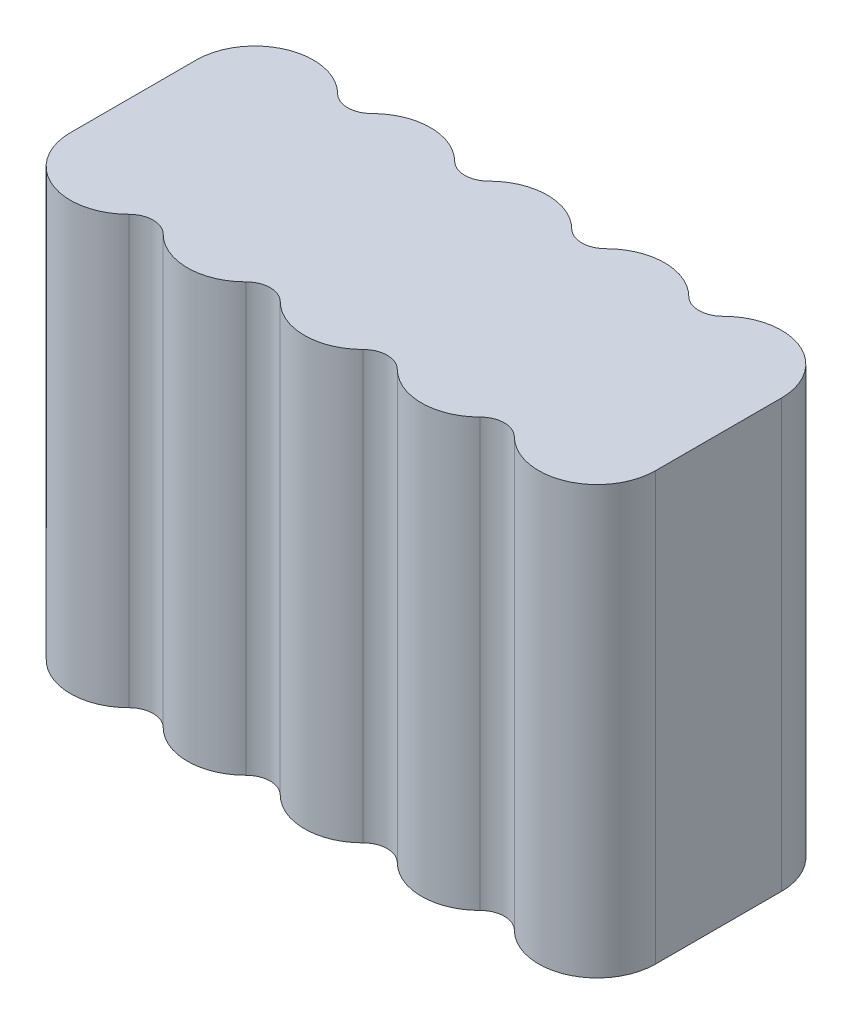
SolidWorks part; units mm, degrees
ref_plane "Front Plane" through (0, 0, 0) normal (0, 0, 1) x (1, 0, 0)
ref_plane "Top Plane" through (0, 0, 0) normal (0, 1, 0) x (1, 0, 0)
ref_plane "Right Plane" through (0, 0, 0) normal (1, 0, 0) x (0, 0, -1)
sketch "Sketch1" plane through (0, 0, 0) normal (0, 1, 0) x (1, 0, 0)
  line L0 (0, 23.139) -> (0, 7.341)
  line L1 (0, 0) -> (73.406, 0) construction
  line L2 (0, 0) -> (0, 30.48) construction
  line L3 (0, 30.48) -> (73.406, 30.48) construction
  line L4 (73.406, 0) -> (73.406, 30.48) construction
  line L5 (73.406, 23.139) -> (73.406, 7.341)
  arc A0 (14.6815, 23.0533) -> (14.6815, 23.2247) centre (7.341, 23.139) ccw
  arc A1 (0, 7.341) -> (12.5317, 2.15) centre (7.341, 7.341) ccw
  arc A2 (29.3625, 23.0533) -> (29.3625, 23.2247) centre (22.022, 23.139) ccw
  arc A3 (14.6815, 7.4267) -> (14.6815, 7.2553) centre (22.022, 7.341) ccw
  arc A4 (44.0435, 23.0533) -> (44.0435, 23.2247) centre (36.703, 23.139) ccw
  arc A5 (29.3625, 7.4267) -> (29.3625, 7.2553) centre (36.703, 7.341) ccw
  arc A6 (58.7245, 23.0533) -> (58.7245, 23.2247) centre (51.384, 23.139) ccw
  arc A7 (44.0435, 7.4267) -> (44.0435, 7.2553) centre (51.384, 7.341) ccw
  arc A8 (73.406, 23.139) -> (60.8743, 28.33) centre (66.065, 23.139) ccw
  arc A9 (58.7245, 7.4267) -> (58.7245, 7.2553) centre (66.065, 7.341) ccw
  arc A10 (12.5317, 28.33) -> (16.8313, 28.33) centre (14.6815, 30.48) ccw
  arc A11 (27.2127, 28.33) -> (31.5123, 28.33) centre (29.3625, 30.48) ccw
  arc A12 (41.8937, 28.33) -> (46.1933, 28.33) centre (44.0435, 30.48) ccw
  arc A13 (56.5747, 28.33) -> (60.8743, 28.33) centre (58.7245, 30.48) ccw
  arc A14 (16.8313, 2.15) -> (12.5317, 2.15) centre (14.6815, 0) ccw
  arc A15 (31.5123, 2.15) -> (27.2127, 2.15) centre (29.3625, 0) ccw
  arc A16 (46.1933, 2.15) -> (41.8937, 2.15) centre (44.0435, 0) ccw
  arc A17 (60.8743, 2.15) -> (56.5747, 2.15) centre (58.7245, 0) ccw
  arc A18 (12.5317, 28.33) -> (0, 23.139) centre (7.341, 23.139) ccw
  arc A19 (14.6815, 23.2247) -> (14.6815, 23.0533) centre (22.022, 23.139) ccw
  arc A20 (27.2127, 28.33) -> (16.8313, 28.33) centre (22.022, 23.139) ccw
  arc A21 (29.3625, 23.2247) -> (29.3625, 23.0533) centre (36.703, 23.139) ccw
  arc A22 (41.8937, 28.33) -> (31.5123, 28.33) centre (36.703, 23.139) ccw
  arc A23 (44.0435, 23.2247) -> (44.0435, 23.0533) centre (51.384, 23.139) ccw
  arc A24 (56.5747, 28.33) -> (46.1933, 28.33) centre (51.384, 23.139) ccw
  arc A25 (58.7245, 23.2247) -> (58.7245, 23.0533) centre (66.065, 23.139) ccw
  arc A26 (60.8743, 2.15) -> (73.406, 7.341) centre (66.065, 7.341) ccw
  arc A27 (58.7245, 7.2553) -> (58.7245, 7.4267) centre (51.384, 7.341) ccw
  arc A28 (46.1933, 2.15) -> (56.5747, 2.15) centre (51.384, 7.341) ccw
  arc A29 (44.0435, 7.2553) -> (44.0435, 7.4267) centre (36.703, 7.341) ccw
  arc A30 (31.5123, 2.15) -> (41.8937, 2.15) centre (36.703, 7.341) ccw
  arc A31 (29.3625, 7.2553) -> (29.3625, 7.4267) centre (22.022, 7.341) ccw
  arc A32 (16.8313, 2.15) -> (27.2127, 2.15) centre (22.022, 7.341) ccw
  arc A33 (14.6815, 7.2553) -> (14.6815, 7.4267) centre (7.341, 7.341) ccw
  dimension "D3" = 14.682
  dimension "D1" = 73.406
  dimension "D2" = 30.48
  dimension "D4" = 5
extrude "Boss-Extrude1" add sketch "Sketch1" along normal blind 53.594
